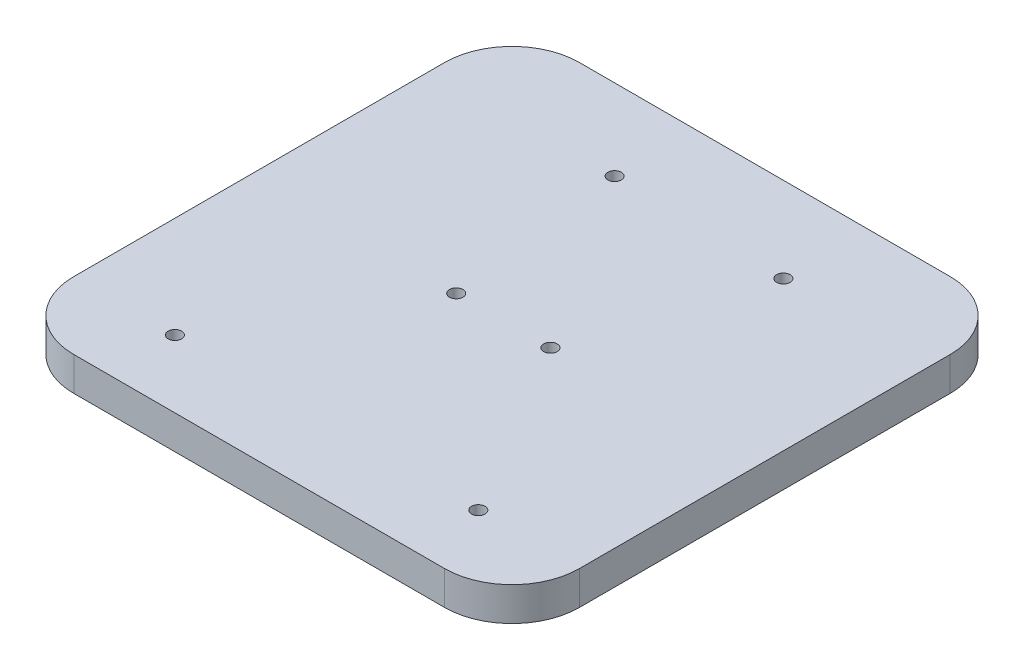
SolidWorks part; units mm, degrees
ref_plane "Front Plane" through (0, 0, 0) normal (0, 0, 1) x (1, 0, 0)
ref_plane "Top Plane" through (0, 0, 0) normal (0, 1, 0) x (1, 0, 0)
ref_plane "Right Plane" through (0, 0, 0) normal (1, 0, 0) x (0, 0, -1)
sketch "Sketch1" plane through (0, 0, 0) normal (0, 1, 0) x (1, 0, 0)
  line L0 (30, 20) -> (120, 20) construction
  line L1 (0, 0) -> (150, 0)
  line L2 (0, 0) -> (0, 150)
  line L3 (0, 150) -> (150, 150)
  line L4 (150, 0) -> (150, 150)
  line L5 (61.03, 72.42) -> (88.97, 72.42) construction
  circle A0 centre (30, 20) radius 2
  circle A1 centre (120, 20) radius 2
  circle A2 centre (61.03, 72.42) radius 2
  circle A3 centre (88.97, 72.42) radius 2
  circle A4 centre (105.74, 124.76) radius 2
  circle A5 centre (54.4, 126.03) radius 2
  point P9 (75, 20)
  point P10 (75, 0)
  point P19 (75, 72.42)
  point P20 (75, 150)
  dimension "D3" = 4
  dimension "D5" = 20
  dimension "D6" = 27.94
  dimension "D7" = 23.97
  dimension "D9" = 53.61
  dimension "D10" = 6.63
  dimension "D1" = 150
  dimension "D2" = 150
  dimension "D4" = 90
  dimension "D8" = 25.24
  dimension "D11" = 16.77
extrude "Boss-Extrude1" add sketch "Sketch1" along normal blind 10
sketch "Sketch2" plane through (0, 0, 0) normal (0, -1, 0) x (1, 0, 0)
  circle A0 centre (30, -20) radius 4
  circle A1 centre (120, -20) radius 4
  circle A2 centre (88.97, -72.42) radius 4
  circle A3 centre (61.03, -72.42) radius 4
  circle A4 centre (54.4, -126.03) radius 4
  circle A5 centre (105.74, -124.76) radius 4
  dimension "D1" = 8
extrude "Cut-Extrude1" cut sketch "Sketch2" against normal blind 5
fillet "Fillet1" radius 20 4 edges at (0, 5, -150) (150, 5, -150) (150, 5, 0) (0, 5, 0)
